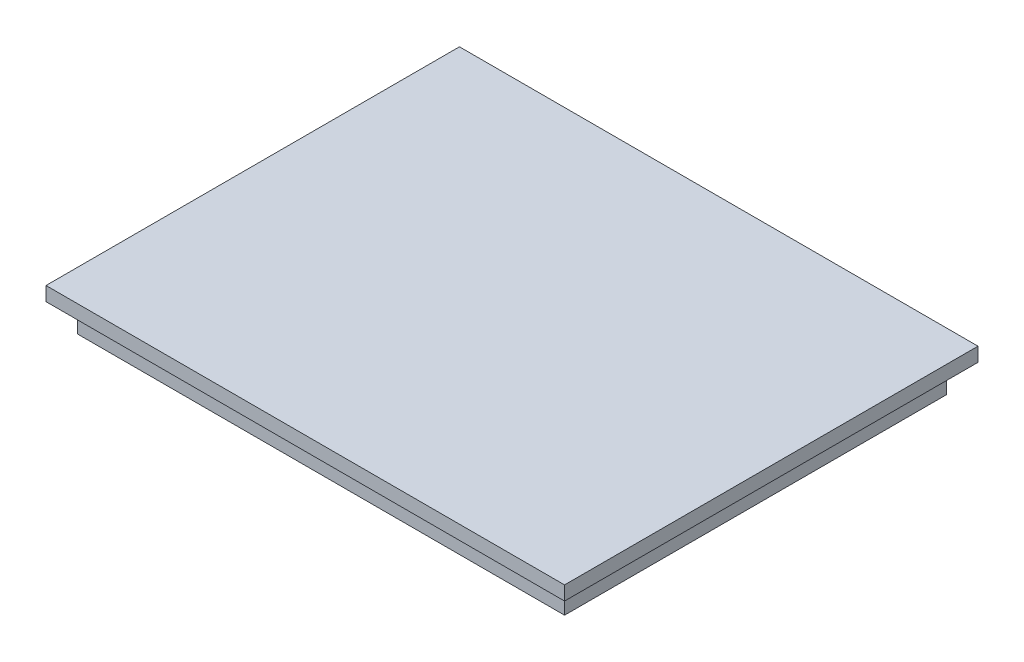
SolidWorks part; units mm, degrees
ref_plane "Front Plane" through (0, 0, 0) normal (0, 0, 1) x (1, 0, 0)
ref_plane "Top Plane" through (0, 0, 0) normal (0, 1, 0) x (1, 0, 0)
ref_plane "Right Plane" through (0, 0, 0) normal (1, 0, 0) x (0, 0, -1)
sketch "Sketch1" plane through (0, 0, 0) normal (0, 1, 0) x (1, 0, 0)
  line L1 (-37, -29.5) -> (37, -29.5)
  line L2 (-37, -29.5) -> (-37, 29.5)
  line L3 (-37, 29.5) -> (37, 29.5)
  line L4 (37, -29.5) -> (37, 29.5)
  line L5 (-37, -29.5) -> (37, 29.5) construction
  line L6 (-37, 29.5) -> (37, -29.5) construction
  point P0 (0, 0)
  dimension "D1" = 74
  dimension "D2" = 59
extrude "Boss-Extrude1" add sketch "Sketch1" along normal blind 2
sketch "Sketch2" plane through (0, 0, 0) normal (0, -1, 0) x (1, 0, 0)
  line L1 (-34.75, -27.25) -> (34.75, -27.25)
  line L2 (-34.75, -27.25) -> (-34.75, 27.25)
  line L3 (-34.75, 27.25) -> (34.75, 27.25)
  line L4 (34.75, -27.25) -> (34.75, 27.25)
  line L5 (-34.75, -27.25) -> (34.75, 27.25) construction
  line L6 (-34.75, 27.25) -> (34.75, -27.25) construction
  line L7 (-32.75, -25.25) -> (32.75, -25.25)
  line L8 (-32.75, -25.25) -> (-32.75, 25.25)
  line L9 (-32.75, 25.25) -> (32.75, 25.25)
  line L10 (32.75, -25.25) -> (32.75, 25.25)
  line L11 (-32.75, -25.25) -> (32.75, 25.25) construction
  line L12 (-32.75, 25.25) -> (32.75, -25.25) construction
  point P0 (0, 0)
  point P6 (0, 0)
  dimension "D1" = 69.5
  dimension "D2" = 54.5
  dimension "D3" = 65.5
  dimension "D4" = 50.5
extrude "Boss-Extrude2" add sketch "Sketch2" along normal blind 4 contours L1 L4 L3 L2 L10 L7 L8 L9
